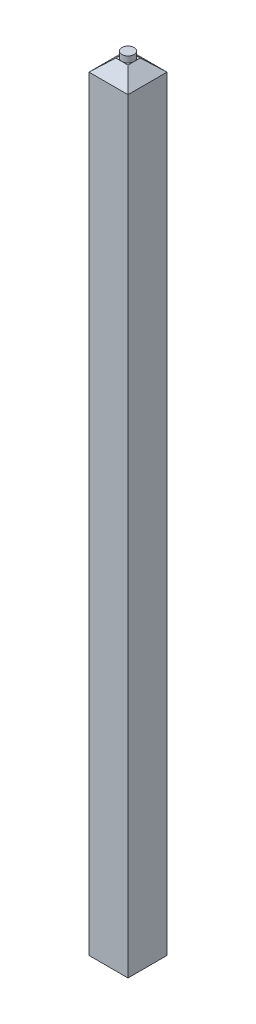
SolidWorks part; units mm, degrees
ref_plane "Front Plane" through (0, 0, 0) normal (0, 0, 1) x (1, 0, 0)
ref_plane "Top Plane" through (0, 0, 0) normal (0, 1, 0) x (1, 0, 0)
ref_plane "Right Plane" through (0, 0, 0) normal (1, 0, 0) x (0, 0, -1)
sketch "Sketch1" plane through (0, 0, 0) normal (0, 1, 0) x (1, 0, 0)
  line L1 (-0.32, 0.32) -> (0.32, 0.32)
  line L2 (-0.32, 0.32) -> (-0.32, -0.32)
  line L3 (-0.32, -0.32) -> (0.32, -0.32)
  line L4 (0.32, 0.32) -> (0.32, -0.32)
  line L5 (-0.32, 0.32) -> (0.32, -0.32) construction
  line L6 (-0.32, -0.32) -> (0.32, 0.32) construction
  point P0 (0, 0)
  dimension "D1" = 0.64
  dimension "D2" = 0.64
extrude "Boss-Extrude1" add sketch "Sketch1" along normal blind 12.54
ref_plane "Plane1" through (0, 12.74, 0) normal (0, 1, 0) x (1, 0, 0)
sketch "Sketch3" plane through (0, 12.74, 0) normal (0, 1, 0) x (1, 0, 0)
  line L1 (0.1, 0.1) -> (-0.1, 0.1)
  line L2 (0.1, 0.1) -> (0.1, -0.1)
  line L3 (0.1, -0.1) -> (-0.1, -0.1)
  line L4 (-0.1, 0.1) -> (-0.1, -0.1)
  line L5 (0.1, 0.1) -> (-0.1, -0.1) construction
  line L6 (0.1, -0.1) -> (-0.1, 0.1) construction
  point P0 (0, 0)
  dimension "D1" = 0.2
  dimension "D2" = 0.2
loft "Loft1" add profiles "Sketch3" section "Sketch3" section face at (0, 12.54, 0)
ref_plane "Plane2" through (0, -0.2, 0) normal (0, -1, 0) x (-1, 0, 0)
sketch "Sketch4" plane through (0, -0.2, 0) normal (0, -1, 0) x (-1, 0, 0)
  line L1 (0.1, 0.1) -> (-0.1, 0.1)
  line L2 (0.1, 0.1) -> (0.1, -0.1)
  line L3 (0.1, -0.1) -> (-0.1, -0.1)
  line L4 (-0.1, 0.1) -> (-0.1, -0.1)
  line L5 (0.1, 0.1) -> (-0.1, -0.1) construction
  line L6 (0.1, -0.1) -> (-0.1, 0.1) construction
  point P0 (0, 0)
  dimension "D1" = 0.2
  dimension "D2" = 0.2
loft "Loft2" add profiles "Sketch4" section "Sketch4" section face at (0, 0, 0)
sketch "Sketch5" plane through (0, 12.74, 0) normal (0, 1, 0) x (1, 0, 0)
  circle A0 centre (0, 0) radius 0.1
extrude "Boss-Extrude2" add sketch "Sketch5" along normal blind 0.1 contours A0
